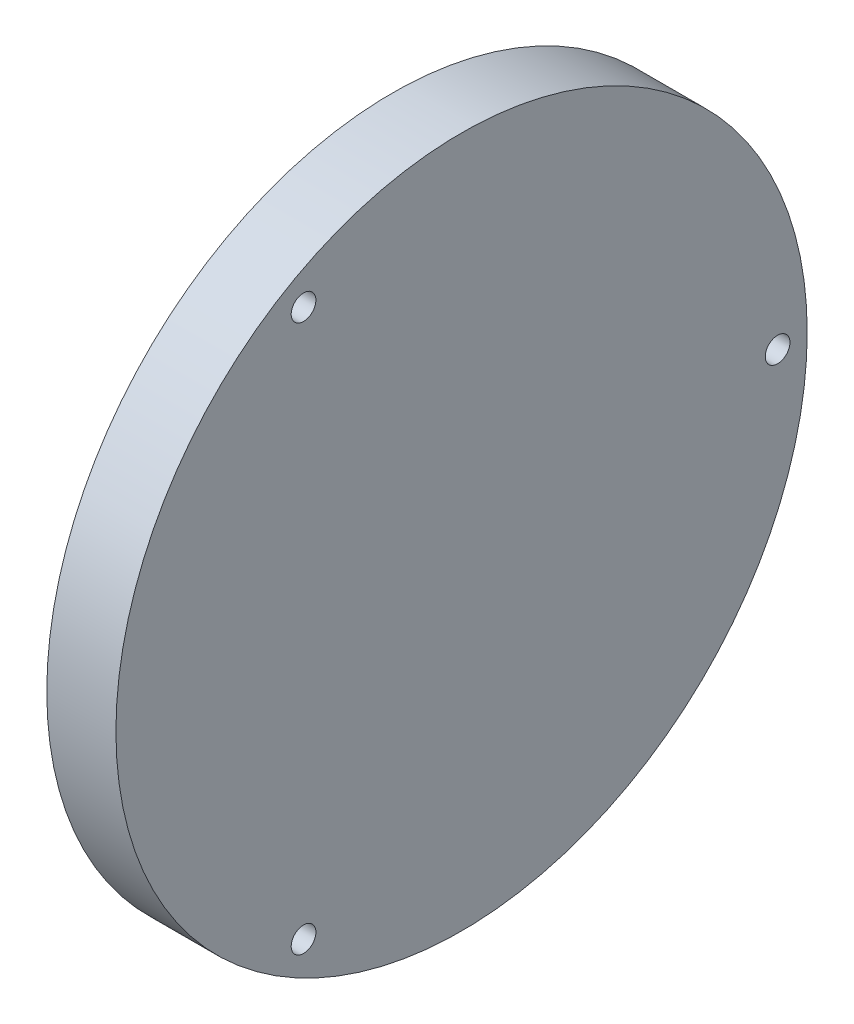
SolidWorks part; units mm, degrees
material "Copper"
ref_plane "Front Plane" through (0, 0, 0) normal (0, 0, 1) x (1, 0, 0)
ref_plane "Top Plane" through (0, 0, 0) normal (0, 1, 0) x (1, 0, 0)
ref_plane "Right Plane" through (0, 0, 0) normal (1, 0, 0) x (0, 0, -1)
sketch "Blank OD70 thickness7 mm" plane through (0, 0, 0) normal (0, 0, 1) x (1, 0, 0)
  line L0 (-10, 0) -> (20, 0) construction
  line L1 (0, 0) -> (7, 0)
  line L2 (7, 0) -> (7, 35)
  line L3 (7, 35) -> (0, 35)
  line L4 (0, 35) -> (0, 0)
revolve "Copper blank - OD70 x7" add sketch "Blank OD70 thickness7 mm" angle 360 about L0
sketch "Water passage R11-25 depth3 round-end C sketch" plane through (0, 0, 0) normal (1, 0, 0) x (0, 0, -1)
  arc A0 (-12.5, 21.6506) -> (12.5, 21.6506) centre (0, 0) ccw
  arc A1 (12.5, 21.6506) -> (5.5, 9.5263) centre (9, 15.5885) ccw
  arc A2 (5.5, 9.5263) -> (-5.5, 9.5263) centre (0, 0) cw
  arc A3 (-5.5, 9.5263) -> (-12.5, 21.6506) centre (-9, 15.5885) ccw
extrude "Water passage R11-25 depth3 round-end C" cut sketch "Water passage R11-25 depth3 round-end C sketch" along normal blind 3 from offset 0
sketch "Inner face-seal gland width2p6 depth1p5 sketch" plane through (0, 0, 0) normal (1, 0, 0) x (0, 0, -1)
  circle A0 centre (0, 0) radius 6.7
  circle A1 centre (0, 0) radius 9.3
extrude "Inner face-seal gland width2p6 depth1p5" cut sketch "Inner face-seal gland width2p6 depth1p5 sketch" along normal blind 1.5 from offset 0
sketch "Outer face-seal gland width2p6 depth1p5 sketch" plane through (0, 0, 0) normal (1, 0, 0) x (0, 0, -1)
  circle A0 centre (0, 0) radius 26.7
  circle A1 centre (0, 0) radius 29.3
extrude "Outer face-seal gland width2p6 depth1p5" cut sketch "Outer face-seal gland width2p6 depth1p5 sketch" along normal blind 1.5 from offset 0
sketch "Six rear cover M3 pilot bores depth4 sketch" plane through (0, 0, 0) normal (1, 0, 0) x (0, 0, -1)
  circle A0 centre (0, 32) radius 1.25
  circle A1 centre (-27.7128, 16) radius 1.25
  circle A2 centre (-27.7128, -16) radius 1.25
  circle A3 centre (0, -32) radius 1.25
  circle A4 centre (27.7128, -16) radius 1.25
  circle A5 centre (27.7128, 16) radius 1.25
extrude "Six rear cover M3 pilot bores depth4" cut sketch "Six rear cover M3 pilot bores depth4 sketch" along normal blind 4 from offset 0
sketch "Three front clamp M3 pilot bores depth3 sketch" plane through (0, 0, 0) normal (1, 0, 0) x (0, 0, -1)
  circle A0 centre (-16, 27.7128) radius 1.25
  circle A1 centre (-16, -27.7128) radius 1.25
  circle A2 centre (32, 0) radius 1.25
extrude "Three front clamp M3 pilot bores depth3" cut sketch "Three front clamp M3 pilot bores depth3 sketch" along normal blind 3 from offset 4
